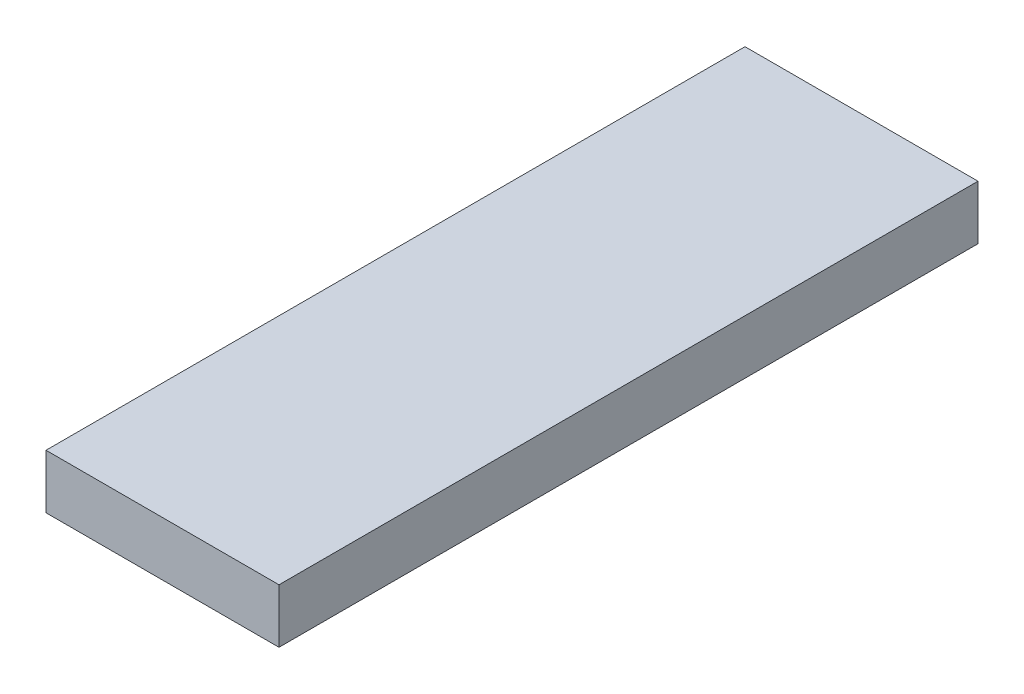
SolidWorks part; units mm, degrees
material "Mahogany"
ref_plane "Front Plane" through (0, 0, 0) normal (0, 0, 1) x (1, 0, 0)
ref_plane "Top Plane" through (0, 0, 0) normal (0, 1, 0) x (1, 0, 0)
ref_plane "Right Plane" through (0, 0, 0) normal (1, 0, 0) x (0, 0, -1)
sketch "Base_Sketch" plane through (0, 0, 0) normal (0, 1, 0) x (1, 0, 0)
  line L0 (-223.2989, 1218.2231) -> (-172.4989, 1218.2231) construction
  line L1 (-223.2989, 1294.4231) -> (-172.4989, 1294.4231)
  line L2 (-223.2989, 1294.4231) -> (-223.2989, 1142.0231)
  line L3 (-223.2989, 1142.0231) -> (-172.4989, 1142.0231)
  line L4 (-172.4989, 1294.4231) -> (-172.4989, 1142.0231)
  line L5 (-223.2989, 1294.4231) -> (-172.4989, 1142.0231) construction
  line L6 (-223.2989, 1142.0231) -> (-172.4989, 1294.4231) construction
  line L7 (-211.4889, 1153.8331) -> (-184.3089, 1153.8331) construction
  line L8 (-184.3089, 1282.6131) -> (-184.3089, 1153.8331) construction
  line L9 (-211.4889, 1282.6131) -> (-184.3089, 1282.6131) construction
  line L10 (-211.4889, 1282.6131) -> (-211.4889, 1153.8331) construction
  line L11 (-235.1089, 1130.2131) -> (-160.6889, 1130.2131) construction
  line L12 (-160.6889, 1306.2331) -> (-160.6889, 1130.2131) construction
  line L13 (-235.1089, 1306.2331) -> (-160.6889, 1306.2331) construction
  line L14 (-235.1089, 1306.2331) -> (-235.1089, 1130.2131) construction
  line L16 (398.1111, 1142.0231) -> (-211.4889, 1142.0231) construction
  line L17 (398.1111, 1294.4231) -> (-211.4889, 1294.4231) construction
  point P0 (-197.8989, 1218.2231)
  dimension "D1" = 50.8
  dimension "D2" = 11.81
  dimension "D3" = 11.81
extrude "Boss-Extrude1" add sketch "Base_Sketch" along normal blind 11.81
equation "\"Material_Thickness\"= \"Material_Thickness@Petrov.Assembly\""
equation "\"D1@Boss-Extrude1\"=\"Material_Thickness\""
equation "\"Width\"= \"Accent_Width@Petrov.Assembly\""
equation "\"D1@Base_Sketch\"=\"Width\""
equation "\"D2@Base_Sketch\"=\"Material_Thickness\""
equation "\"D3@Base_Sketch\"=\"Material_Thickness\""
